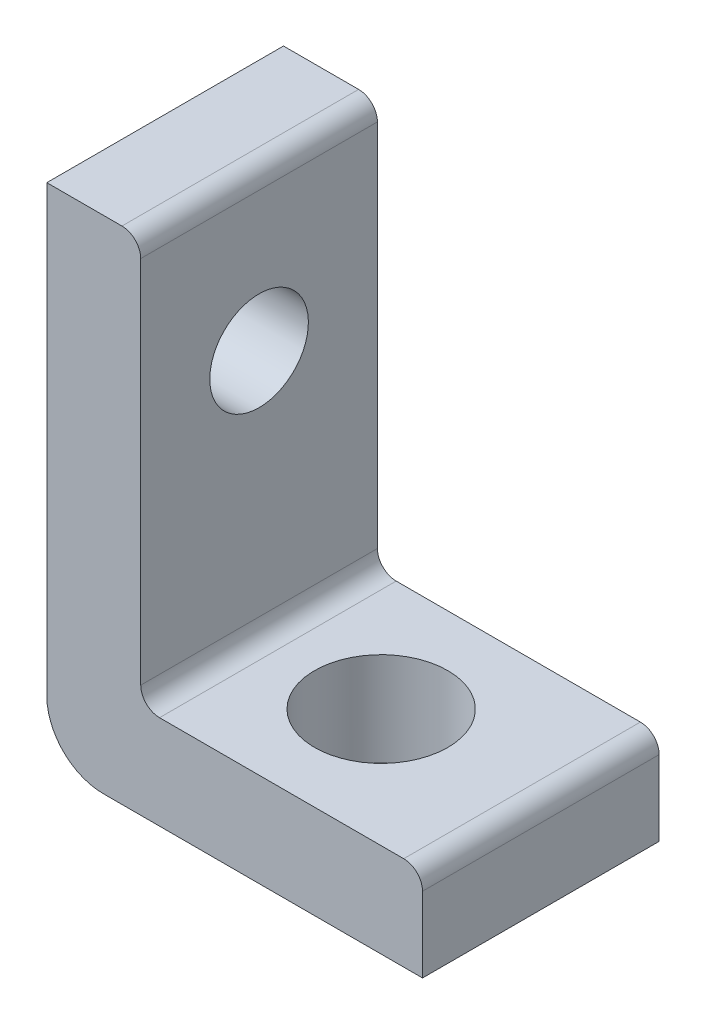
SolidWorks part; units mm, degrees
material "A-Glass Fiber"
ref_plane "Front Plane" through (0, 0, 0) normal (0, 0, 1) x (1, 0, 0)
ref_plane "Top Plane" through (0, 0, 0) normal (0, 1, 0) x (1, 0, 0)
ref_plane "Right Plane" through (0, 0, 0) normal (1, 0, 0) x (0, 0, -1)
sketch "Sketch1" plane through (0, 0, 0) normal (0, 0, 1) x (1, 0, 0)
  line L0 (0, 25.4) -> (0, 0) construction
  line L1 (0, 0) -> (19.05, 0) construction
  line L2 (19.05, 0) -> (19.05, 4.7625) construction
  line L3 (19.05, 4.7625) -> (4.7625, 4.7625) construction
  line L4 (4.7625, 4.7625) -> (4.7625, 25.4) construction
  line L6 (4.7625, 25.4) -> (0, 25.4) construction
  point P4 (0, 0)
  dimension "Outside Height" = 25.4
  dimension "Inside Height" = 20.6375
  dimension "Outside Width" = 19.05
  dimension "Inside Width" = 14.2875
  dimension "Wall Thickness" = 4.7625
sketch "Sketch2" plane through (0, 0, 0) normal (1, 0, 0) x (0, 0, -1)
  line L0 (6, 25.4) -> (-6, 25.4) construction
  point P0 (15.9075, 25.4)
  point P4 (0, 0)
  point P6 (-15.9075, 25.4)
  point P7 (0, 25.4)
  dimension "Length" = 12
  dimension "D1" = 21.9075
  dimension "D2" = 21.9075
sketch "Sketch3" plane through (0, 0, 0) normal (0, 0, 1) x (1, 0, 0)
  line L0 (4.7625, 25.4) -> (0, 25.4)
  line L1 (0, 25.4) -> (0, 0)
  line L2 (0, 0) -> (19.05, 0)
  line L3 (19.05, 0) -> (19.05, 4.7625)
  line L4 (19.05, 4.7625) -> (4.7625, 4.7625)
  line L5 (4.7625, 4.7625) -> (4.7625, 25.4)
extrude "Boss-Extrude1" add sketch "Sketch3" along normal mid plane 12
fillet "Fillet1" radius 0.9525 3 edges at (19.05, 4.7625, 0) (4.7625, 25.4, 0) (4.7625, 4.7625, 0)
fillet "Fillet2" radius 2.8575 1 edges at (0, 0, 0)
sketch "Sketch4" plane through (0, 0, 0) normal (0, -1, 0) x (1, 0, 0)
  line L0 (2.8575, 6) -> (19.05, 6) construction
  point P0 (10.9537, 0)
  point P3 (10.9537, 6)
hole_wizard "1/4 Clearance Hole1" positions "Sketch5" profile "Sketch6" hole size "1/4" standard "ANSI Inch" end condition through all
sketch "Sketch5" plane through (0, 0, 0) normal (0, -1, 0) x (-1, 0, 0)
  point P0 (-10.9537, 0)
sketch "Sketch6" plane through (10.9537, 0, 0) normal (1, 0, 0) x (0, 0, -1)
  line L0 (0, 0) -> (0, 25.4)
  line L1 (0, 25.4) -> (3.3782, 25.4)
  line L2 (3.3782, 25.4) -> (3.3782, 0)
  line L5 (3.3782, 0) -> (0, 0)
  line L11 (0, -6.35) -> (0, 107.95) construction
  dimension "Thru Hole Dia." = 6.7564
  dimension "Thru Hole Depth" = 25.4
sketch "Sketch7" plane through (0, 0, 0) normal (-1, 0, 0) x (0, 0, 1)
  line L0 (6, 25.4) -> (-6, 25.4) construction
  circle A0 centre (0, 17.4) radius 2.5
  point P1 (0, 0)
  dimension "D2" = 5
  dimension "D1" = 8
extrude "Cut-Extrude1" cut sketch "Sketch7" against normal up to next
equation "\"D1@Boss-Extrude1\"=\"Length@Sketch2\""
equation "\"D1@Sketch2\" = \"Outside Width@Sketch1\" * 1.15"
equation "\"D2@Sketch2\"=\"D1@Sketch2\""
equation "\"D1@Fillet1\"=\"Wall Thickness@Sketch1\"*.2"
equation "\"D1@Fillet2\"=\"Wall Thickness@Sketch1\"*.6"
